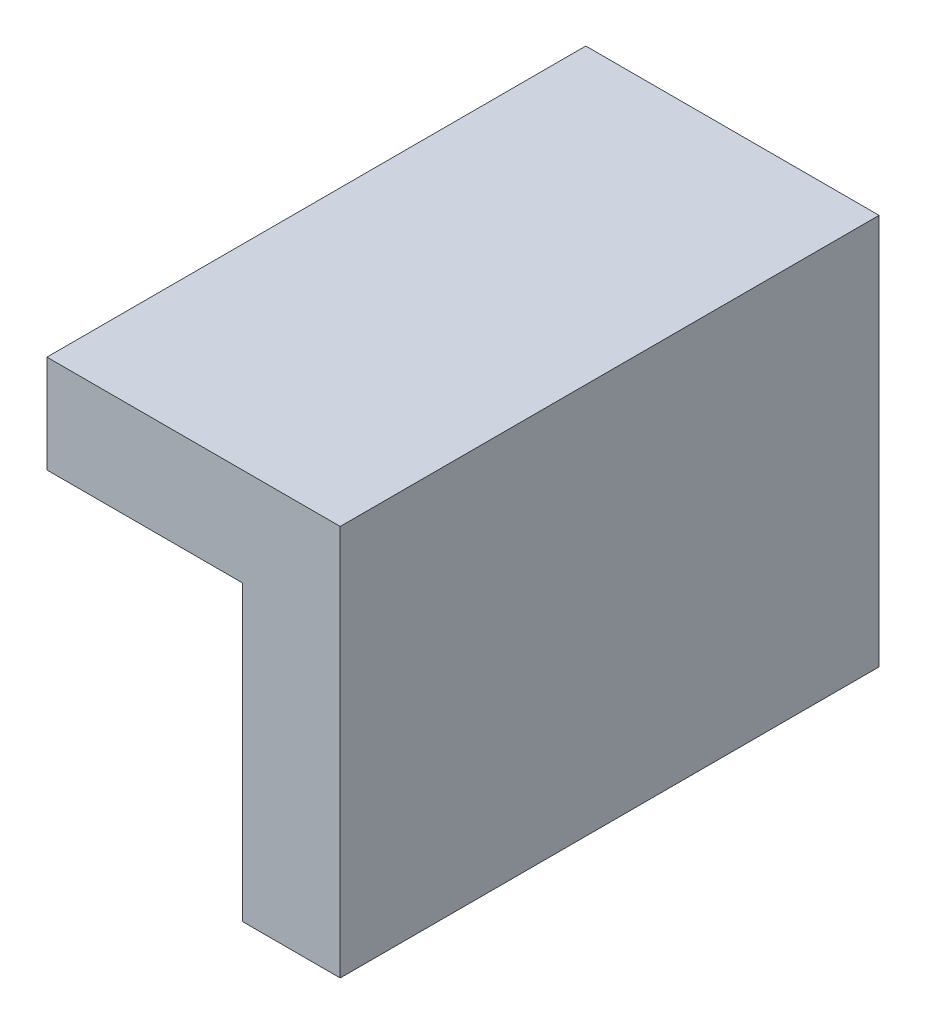
SolidWorks part; units mm, degrees
material "Aleación 1060"
ref_plane "Alzado" through (0, 0, 0) normal (0, 0, 1) x (1, 0, 0)
ref_plane "Planta" through (0, 0, 0) normal (0, 1, 0) x (1, 0, 0)
ref_plane "Vista lateral" through (0, 0, 0) normal (1, 0, 0) x (0, 0, -1)
sketch "Croquis1" plane through (0, 0, 0) normal (0, 0, 1) x (1, 0, 0)
  line L1 (55, -25.4) -> (-55, -25.4)
  line L2 (55, -25.4) -> (55, 25.4)
  line L3 (55, 25.4) -> (-55, 25.4)
  line L4 (-55, -25.4) -> (-55, 25.4)
  line L5 (55, -25.4) -> (-55, 25.4) construction
  line L6 (55, 25.4) -> (-55, -25.4) construction
  point P0 (0, 0)
  dimension "D1" = 50.8
  dimension "D2" = 110
extrude "Saliente-Extruir1" add sketch "Croquis1" along normal blind 12.7
sketch "Croquis2" plane through (0, 0, 0) normal (0, 0, -1) x (-1, 0, 0)
  line L1 (-55, -25.4) -> (-4.2, -25.4)
  line L2 (-55, -25.4) -> (-55, 194.6)
  line L3 (-55, 194.6) -> (-4.2, 194.6)
  line L4 (-4.2, -25.4) -> (-4.2, 194.6)
  dimension "D1" = 50.8
  dimension "D2" = 220
extrude "Saliente-Extruir2" add sketch "Croquis2" along normal blind 12.7
sketch "Croquis4" plane through (0, 0, -12.7) normal (0, 0, -1) x (-1, 0, 0)
  line L1 (-55, 194.6) -> (-42.3, 194.6)
  line L2 (-55, 194.6) -> (-55, 143.8)
  line L3 (-55, 143.8) -> (-42.3, 143.8)
  line L4 (-42.3, 194.6) -> (-42.3, 143.8)
  line L5 (-42.3, 194.6) -> (-16.9, 194.6)
  line L6 (-42.3, 194.6) -> (-42.3, 181.9)
  line L7 (-42.3, 181.9) -> (-16.9, 181.9)
  line L8 (-16.9, 194.6) -> (-16.9, 181.9)
  line M5 (-55, 194.6) -> (-55, -25.4)
  line M8 (-4.2, 194.6) -> (-55, 194.6)
  dimension "D1" = 50.8
  dimension "D2" = 12.7
  dimension "D3" = 25.4
  dimension "D4" = 12.7
extrude "Saliente-Extruir3" add sketch "Croquis4" along normal blind 57.3 contours L4 L3 M8 M5 | L8 L4 L7 M8
sketch "Croquis5" plane through (0, 0, -12.7) normal (0, 0, -1) x (-1, 0, 0)
  line L4 (-55, 25.4) -> (-4.2, 25.4)
  line L5 (-55, 194.6) -> (-55, 25.4)
  line L6 (-4.2, 194.6) -> (-55, 194.6)
  line L7 (-4.2, 25.4) -> (-4.2, 194.6)
  line L8 (-55, 25.4) -> (-4.2, 25.4)
  line L9 (-55, 194.6) -> (-55, 25.4)
  line L10 (-4.2, 194.6) -> (-55, 194.6)
  line L11 (-4.2, 25.4) -> (-4.2, 194.6)
  line L12 (55, -25.4) -> (55, 25.4)
  line L13 (-55, -25.4) -> (55, -25.4)
  line L14 (-55, 25.4) -> (-55, -25.4)
  line L15 (55, 25.4) -> (-55, 25.4)
  line L16 (55, -25.4) -> (55, 25.4)
  line L17 (-55, -25.4) -> (55, -25.4)
  line L18 (-55, 25.4) -> (-55, -25.4)
  line L19 (55, 25.4) -> (-55, 25.4)
  line M9 (-42.3, 143.8) -> (-55, 143.8)
  line M10 (-55, 143.8) -> (-55, -25.4)
  line M11 (-55, -25.4) -> (-4.2, -25.4)
  line M12 (-4.2, -25.4) -> (-4.2, 194.6)
  line M13 (-4.2, 194.6) -> (-16.9, 194.6)
  line M14 (-16.9, 194.6) -> (-16.9, 181.9)
  line M15 (-16.9, 181.9) -> (-42.3, 181.9)
  line M16 (-42.3, 181.9) -> (-42.3, 143.8)
  dimension "D1" = 0
  dimension "D2" = 0
extrude "Cortar-Extruir1" cut sketch "Croquis5" against normal through all contours L8 M10 M12 M13 M14 M15 M16 M9 | L8 M10 M11 M12 | L16 L19 L17 M12
